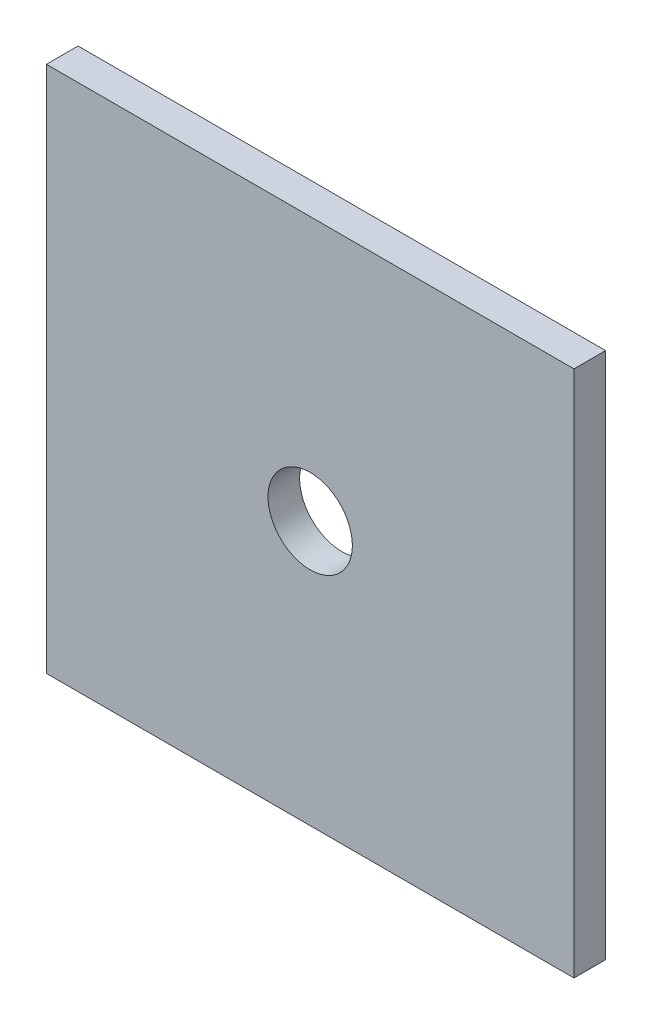
SolidWorks part; units mm, degrees
ref_plane "Alzado" through (0, 0, 0) normal (0, 0, 1) x (1, 0, 0)
ref_plane "Planta" through (0, 0, 0) normal (0, 1, 0) x (1, 0, 0)
ref_plane "Vista lateral" through (0, 0, 0) normal (1, 0, 0) x (0, 0, -1)
sketch "Croquis1" plane through (0, 0, 0) normal (0, 0, 1) x (1, 0, 0)
  line L1 (-25, -25) -> (25, -25)
  line L2 (-25, -25) -> (-25, 25)
  line L3 (-25, 25) -> (25, 25)
  line L4 (25, -25) -> (25, 25)
  line L5 (-25, -25) -> (25, 25) construction
  line L6 (-25, 25) -> (25, -25) construction
  circle A0 centre (0, 0) radius 4
  point P0 (0, 0)
  dimension "D3" = 8
  dimension "D1" = 50
  dimension "D2" = 50
extrude "Saliente-Extruir1" add sketch "Croquis1" along normal blind 3
